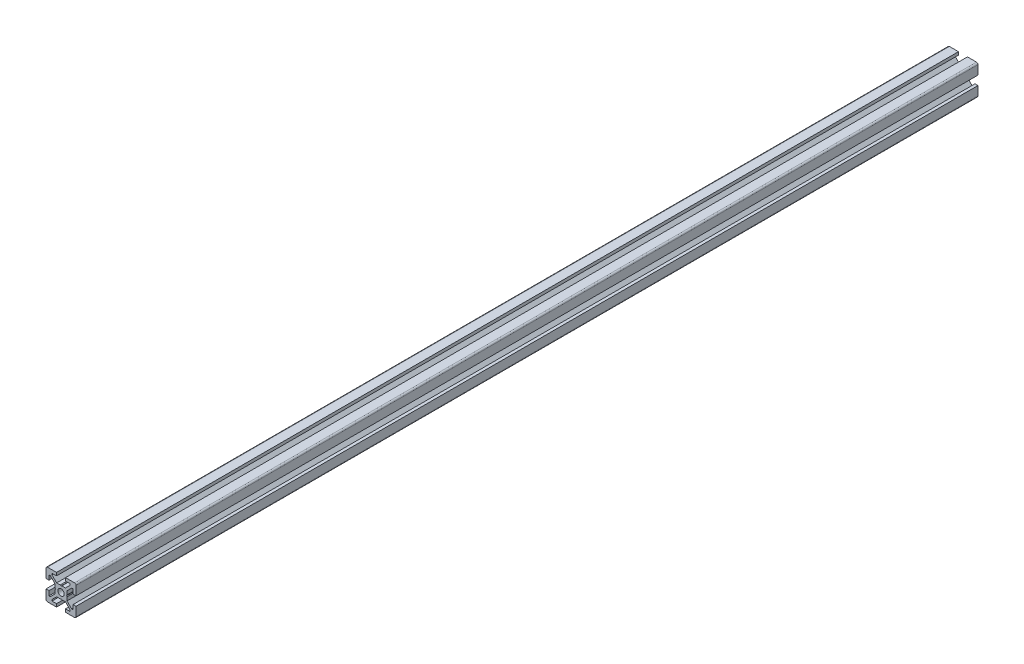
SolidWorks part; units mm, degrees
ref_plane "Front Plane" through (0, 0, 0) normal (0, 0, 1) x (1, 0, 0)
ref_plane "Top Plane" through (0, 0, 0) normal (0, 1, 0) x (1, 0, 0)
ref_plane "Right Plane" through (0, 0, 0) normal (1, 0, 0) x (0, 0, -1)
ref_plane "Plane1" through (0, 0, -500) normal (0, 0, -1) x (-1, 0, 0)
sketch "Sketch1" plane through (0, 0, -500) normal (0, 0, -1) x (-1, 0, 0)
  line L0 (9, 10) -> (3, 10)
  line L1 (3, 10) -> (3, 8)
  line L2 (3, 8) -> (6, 8)
  line L3 (6, 8) -> (6, 7.0607)
  line L4 (6, 7.0607) -> (2.9393, 4)
  line L5 (2.9393, 4) -> (0.5196, 4)
  line L6 (0.5196, 4) -> (0, 3.7)
  line L7 (0, 3.7) -> (-0.5196, 4)
  line L8 (-0.5196, 4) -> (-2.9393, 4)
  line L9 (-2.9393, 4) -> (-6, 7.0607)
  line L10 (-6, 7.0607) -> (-6, 8)
  line L11 (-6, 8) -> (-3, 8)
  line L12 (-3, 8) -> (-3, 10)
  line L13 (-3, 10) -> (-9, 10)
  line L14 (-10, 9) -> (-10, 3)
  line L15 (-10, 3) -> (-8, 3)
  line L16 (-8, 3) -> (-8, 6)
  line L17 (-8, 6) -> (-7.0607, 6)
  line L18 (-7.0607, 6) -> (-4, 2.9393)
  line L19 (-4, 2.9393) -> (-4, 0.5196)
  line L20 (-4, 0.5196) -> (-3.7, 0)
  line L21 (-3.7, 0) -> (-4, -0.5196)
  line L22 (-4, -0.5196) -> (-4, -2.9393)
  line L23 (-4, -2.9393) -> (-7.0607, -6)
  line L24 (-7.0607, -6) -> (-8, -6)
  line L25 (-8, -6) -> (-8, -3)
  line L26 (-8, -3) -> (-10, -3)
  line L27 (-10, -3) -> (-10, -9)
  line L28 (-9, -10) -> (-3, -10)
  line L29 (-3, -10) -> (-3, -8)
  line L30 (-3, -8) -> (-6, -8)
  line L31 (-6, -8) -> (-6, -7.0607)
  line L32 (-6, -7.0607) -> (-2.9393, -4)
  line L33 (-2.9393, -4) -> (-0.5196, -4)
  line L34 (-0.5196, -4) -> (0, -3.7)
  line L35 (0, -3.7) -> (0.5196, -4)
  line L36 (0.5196, -4) -> (2.9393, -4)
  line L37 (2.9393, -4) -> (6, -7.0607)
  line L38 (6, -7.0607) -> (6, -8)
  line L39 (6, -8) -> (3, -8)
  line L40 (3, -8) -> (3, -10)
  line L41 (3, -10) -> (9, -10)
  line L42 (10, -9) -> (10, -3)
  line L43 (10, -3) -> (8, -3)
  line L44 (8, -3) -> (8, -6)
  line L45 (8, -6) -> (7.0607, -6)
  line L46 (7.0607, -6) -> (4, -2.9393)
  line L47 (4, -2.9393) -> (4, -0.5196)
  line L48 (4, -0.5196) -> (3.7, 0)
  line L49 (3.7, 0) -> (4, 0.5196)
  line L50 (4, 0.5196) -> (4, 2.9393)
  line L51 (4, 2.9393) -> (7.0607, 6)
  line L52 (7.0607, 6) -> (8, 6)
  line L53 (8, 6) -> (8, 3)
  line L54 (8, 3) -> (10, 3)
  line L55 (10, 3) -> (10, 9)
  circle A0 centre (0, 0) radius 2.1
  arc A1 (10, 9) -> (9, 10) centre (9, 9) ccw
  arc A2 (-9, 10) -> (-10, 9) centre (-9, 9) ccw
  arc A3 (-10, -9) -> (-9, -10) centre (-9, -9) ccw
  arc A4 (9, -10) -> (10, -9) centre (9, -9) ccw
extrude "Boss-Extrude1" add sketch "Sketch1" against normal blind 600
